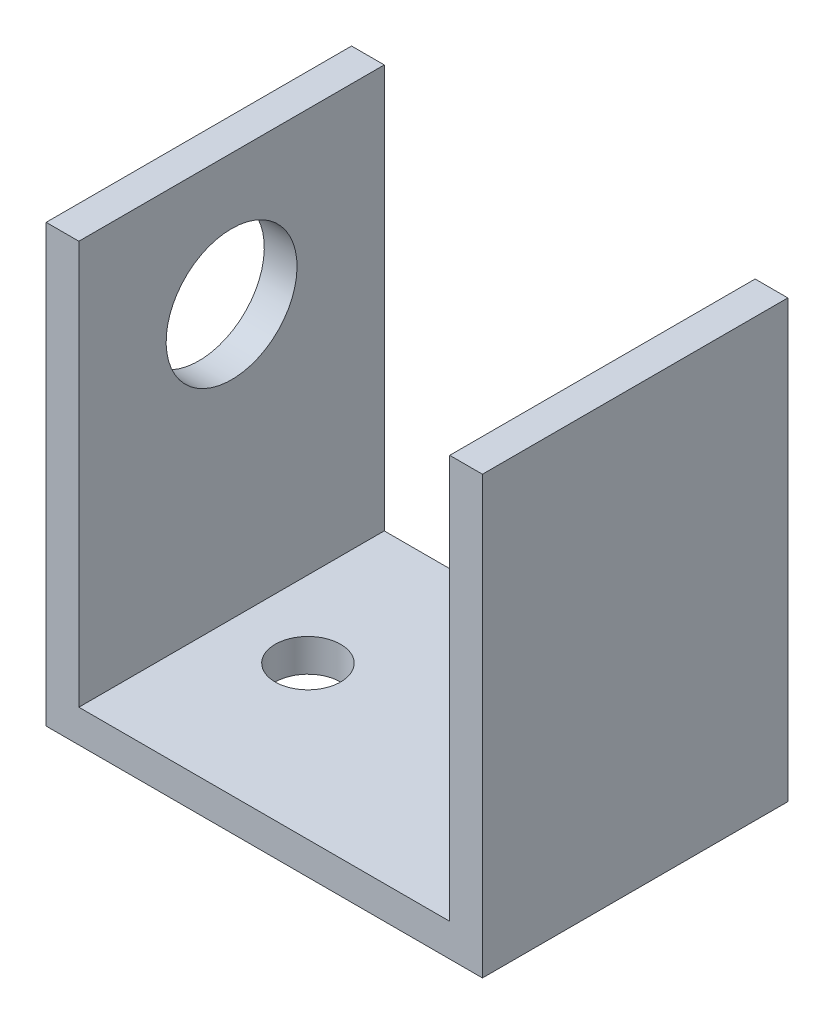
SolidWorks part; units mm, degrees
ref_plane "Plan de face" through (0, 0, 0) normal (0, 0, 1) x (1, 0, 0)
ref_plane "Plan de dessus" through (0, 0, 0) normal (0, 1, 0) x (1, 0, 0)
ref_plane "Plan de droite" through (0, 0, 0) normal (1, 0, 0) x (0, 0, -1)
sketch "Esquisse1" plane through (0, 0, 0) normal (0, 0, 1) x (1, 0, 0)
  line L0 (-31.1486, 3.3838) -> (-29.6486, 3.3838)
  line L1 (-29.6486, 3.3838) -> (-29.6486, -15.1162)
  line L2 (-29.6486, -15.1162) -> (-12.6486, -15.1162)
  line L3 (-11.1486, 3.3838) -> (-11.1486, -16.6162)
  line L4 (-11.1486, -16.6162) -> (-31.1486, -16.6162)
  line L5 (-31.1486, -16.6162) -> (-31.1486, 3.3838)
  line L6 (-12.6486, -15.1162) -> (-12.6486, 3.3838)
  line L7 (-12.6486, 3.3838) -> (-11.1486, 3.3838)
  dimension "D1" = 20
  dimension "D2" = 1.5
  dimension "D3" = 1.5
  dimension "D4" = 20
  dimension "D5" = 1.5
  dimension "D6" = 20
extrude "Extrusion1" add sketch "Esquisse1" along normal blind 14
sketch "Esquisse2" plane through (0, -15.1162, 0) normal (0, 1, 0) x (-1, 0, 0)
  line L1 (31.1486, 14) -> (31.1486, 0) construction
  line L2 (12.6486, 14) -> (29.6486, 14) construction
  line L4 (12.6486, 0) -> (29.6486, 0) construction
  line L5 (11.1486, 14) -> (11.1486, 0) construction
  circle A0 centre (26.1486, 7) radius 1.5
  circle A2 centre (16.1486, 7) radius 1.5
  dimension "D4" = 7
  dimension "D1" = 5
  dimension "D2" = 5
  dimension "D3" = 7
extrude "Extrusion2" cut sketch "Esquisse2" against normal through all
sketch "Esquisse4" plane through (-29.6486, 0, 0) normal (1, 0, 0) x (0, 0, -1)
  line L3 (0, -15.1162) -> (0, 3.3838) construction
  line L4 (-14, 3.3838) -> (0, 3.3838) construction
  circle A0 centre (-7, -2.6162) radius 3
  dimension "D1" = 7
  dimension "D2" = 6
extrude "Extrusion3" cut sketch "Esquisse4" against normal through all
